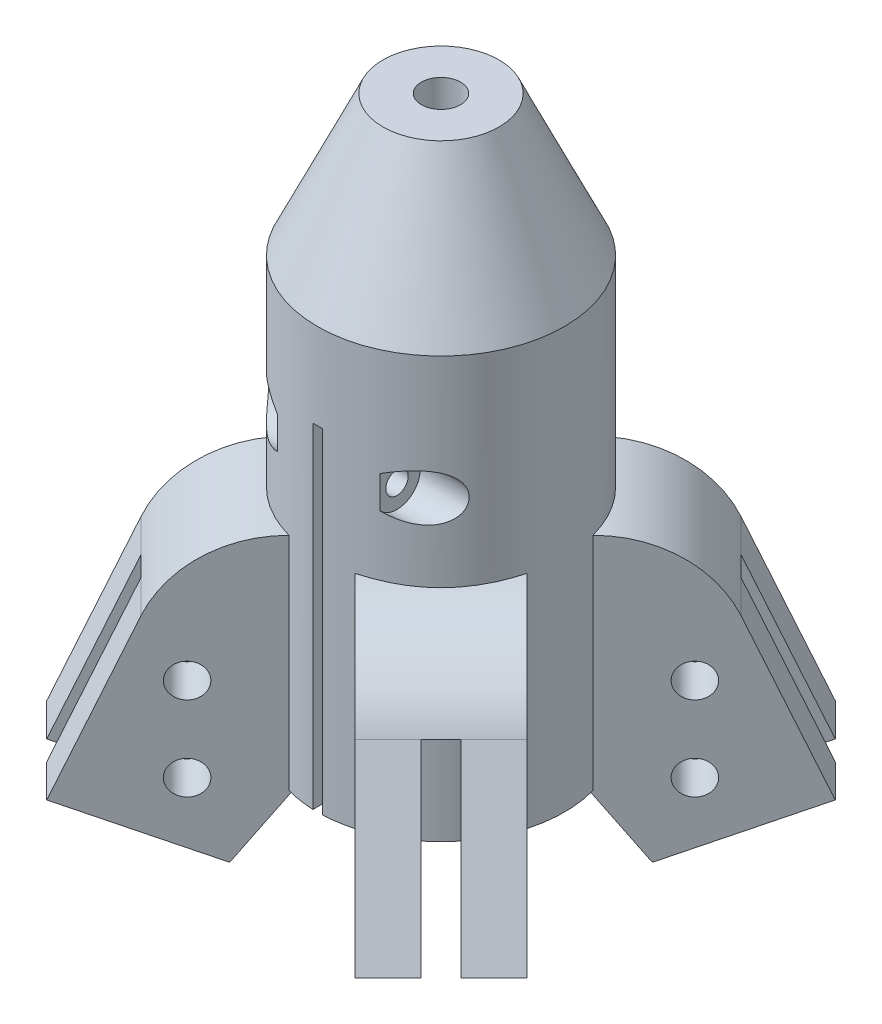
SolidWorks part; units mm, degrees
ref_plane "Front Plane" through (0, 0, 0) normal (0, 0, 1) x (1, 0, 0)
ref_plane "Top Plane" through (0, 0, 0) normal (0, 1, 0) x (1, 0, 0)
ref_plane "Right Plane" through (0, 0, 0) normal (1, 0, 0) x (0, 0, -1)
sketch "Sketch1" plane through (0, 0, 0) normal (0, 1, 0) x (1, 0, 0)
  circle A0 centre (0, 0) radius 2.1
  circle A1 centre (0, 0) radius 13.21
  dimension "D1" = 4.2
  dimension "D2" = 13.21
extrude "Boss-Extrude1" add sketch "Sketch1" along normal blind 20
ref_plane "Plane1" through (0, 0, 0) normal (0.7071, 0, 0.7071) x (0, -1, 0)
chamfer "Chamfer1" distance 1.2 angle 45 1 edges at (0, 0, 2.1)
sketch "Sketch7" plane through (0, 0, 0) normal (0, -1, 0) x (1, 0, 0)
  circle A0 centre (0, 0) radius 3.3 construction
  circle A1 centre (0, 0) radius 3.3
  circle A2 centre (0, 0) radius 13.21 construction
  circle A3 centre (0, 0) radius 13.21
extrude "Boss-Extrude5" add sketch "Sketch7" along normal blind 40
sketch "Sketch8" plane through (0, 0, 0) normal (1, 0, 0) x (0, 0, -1)
  line L0 (-11.21, -4.2) -> (-3.1708, -4.2) construction
  line L1 (-13.21, -4.2) -> (0, -4.2)
  line L2 (-13.21, -4.2) -> (-13.21, -40)
  line L3 (-13.21, -40) -> (0, -40)
  line L4 (0, -4.2) -> (0, -40)
extrude "Cut-Extrude3" cut sketch "Sketch8" along normal up to surface and the other way up to surface
sketch "Sketch11" plane through (0, 0, 0) normal (1, 0, 0) x (0, 0, -1)
  line L1 (0, -4.2) -> (13.21, -4.2)
  line L2 (0, -4.2) -> (0, -40)
  line L3 (0, -40) -> (13.21, -40)
  line L4 (13.21, -4.2) -> (13.21, -40)
  line L5 (-13.2005, -40) -> (13.21, -40) construction
  line L6 (13.21, -40) -> (13.21, 20) construction
extrude "Cut-Extrude5" cut sketch "Sketch11" against normal mid plane 5
sketch "Sketch12" plane through (0.5, 0, 0) normal (-1, 0, 0) x (0, 0, 1)
  circle A0 centre (10.21, -8.2) radius 1.2 construction
  circle A1 centre (10.21, -8.2) radius 1.2
extrude "Cut-Extrude6" cut sketch "Sketch12" against normal through all both and the other way through all
ref_plane "Plane2" through (5.5, 0, 0) normal (-1, 0, 0) x (0, 0, 1)
sketch "Sketch13" plane through (5.5, 0, 0) normal (-1, 0, 0) x (0, 0, 1)
  circle A0 centre (10.21, -8.2) radius 2.5
  circle A1 centre (10.21, -8.2) radius 1.2 construction
  dimension "D1" = 5
extrude "Cut-Extrude7" cut sketch "Sketch13" against normal through all
mirror "Mirror2" about plane through (0, 0, 0) normal (1, 0, 0) of "Cut-Extrude7"
sketch "Sketch15" plane through (-1.0607, 0, -1.0607) normal (-0.7071, 0, -0.7071) x (-0.7071, 0, 0.7071)
  line L0 (-22.7042, -23.8102) -> (-11.21, -23.8102)
  line L3 (-22.7042, -23.8102) -> (-59.1395, -111.0537) construction
  line L7 (-22.7042, -23.8102) -> (-29.8316, -40.8765)
  line L8 (-11.21, -35.211) -> (-11.21, -23.8102)
  line L10 (-15.9902, -46.6571) -> (-29.8316, -40.8765)
  line L11 (-13.21, -40) -> (-11.21, -40) construction
  line L12 (-11.21, -40) -> (-11.21, -35.211)
  line L13 (-3.2909, -40) -> (-10.9398, -40) construction
  line L14 (-15.9902, -46.6571) -> (-11.21, -40)
  line L16 (-42.884, -111.0537) -> (-13.21, -40) construction
  circle A0 centre (-19.21, -29.8102) radius 1.8 construction
  circle A1 centre (-19.21, -38.8102) radius 1.8 construction
  circle A2 centre (-19.21, -29.8102) radius 1.8
  circle A3 centre (-19.21, -38.8102) radius 1.8
  dimension "D1" = 2
  dimension "D2" = 6
extrude "Boss-Extrude6" add sketch "Sketch15" along normal blind 5
ref_plane "Plane3" through (0, 0, 0) normal (0.7071, 0, 0.7071) x (0.7071, 0, -0.7071)
mirror "Mirror3" about plane through (0, 0, 0) normal (0.7071, 0, 0.7071) of "Boss-Extrude6"
sketch "Sketch16" plane through (-4.5962, 0, -4.5962) normal (-0.7071, 0, -0.7071) x (-0.7071, 0, 0.7071)
  line L0 (-22.7042, -23.8102) -> (-29.8316, -40.8765) construction
  line L1 (-22.7042, -23.8102) -> (-29.8316, -40.8765) construction
  line L2 (-11.5002, -23.8102) -> (-11.5002, -40) construction
  line L3 (-11.5002, -23.8102) -> (-11.5002, -40) construction
  line L4 (-11.5002, -23.8102) -> (-22.7042, -23.8102) construction
  line L5 (-11.5002, -23.8102) -> (-22.7042, -23.8102)
  line L6 (-11.5002, -23.8102) -> (-11.5002, -16.3474)
  arc A0 (-22.7042, -23.8102) -> (-11.5002, -16.3474) centre (-11.5002, -28.4893) cw
extrude "Boss-Extrude7" add sketch "Sketch16" against normal up to surface (13 mm away) up to face at (16.9069, -38.8102, -7.7145)
pattern_circular "CirPattern2" count 4 over 360 about axis through (0, 0, 0) along (0, 1, 0) of "Boss-Extrude7", "Mirror3", "Boss-Extrude6"
chamfer "Chamfer2" distance 15 angle 25 1 edges at (0, 20, 13.21)
